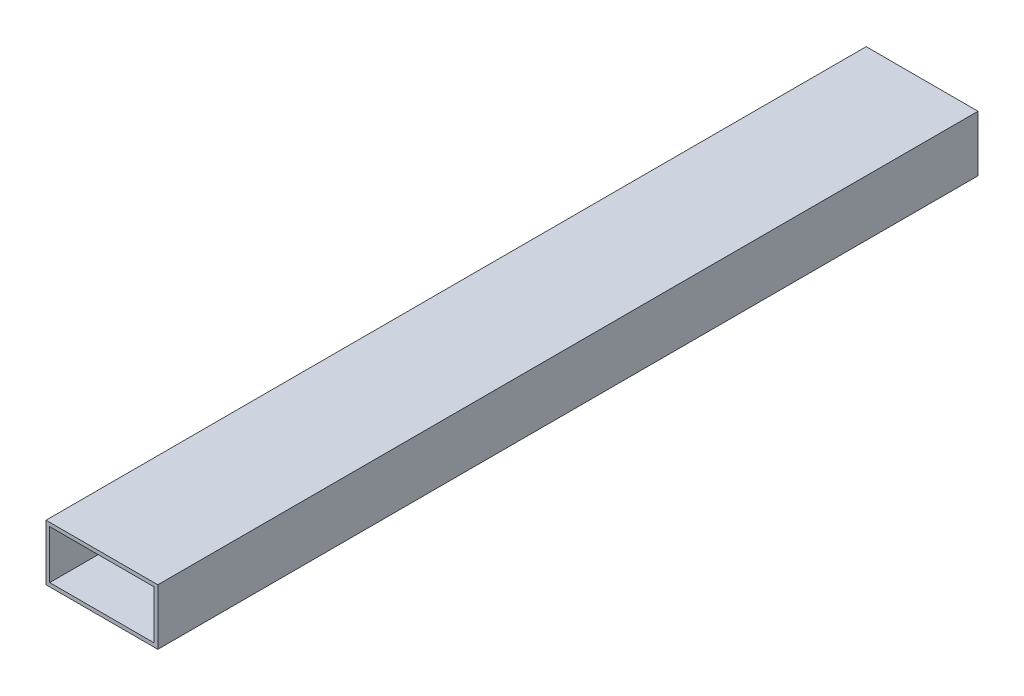
SolidWorks part; units mm, degrees
ref_plane "前视基准面" through (0, 0, 0) normal (0, 0, 1) x (1, 0, 0)
ref_plane "上视基准面" through (0, 0, 0) normal (0, 1, 0) x (1, 0, 0)
ref_plane "右视基准面" through (0, 0, 0) normal (1, 0, 0) x (0, 0, -1)
other "Configuration Table"
sketch "草图1" plane through (0, 0, 0) normal (0, 0, 1) x (1, 0, 0)
  line L0 (1, 1) -> (1, 14)
  line L1 (0, 0) -> (30, 0)
  line L2 (0, 0) -> (0, 15)
  line L3 (0, 15) -> (30, 15)
  line L4 (30, 0) -> (30, 15)
  line L5 (1, 14) -> (29, 14)
  line L6 (29, 1) -> (29, 14)
  line L7 (1, 1) -> (29, 1)
  dimension "D1" = 30
  dimension "D2" = 15
  dimension "D3" = 1
extrude "凸台-拉伸1" add sketch "草图1" along normal blind 220
